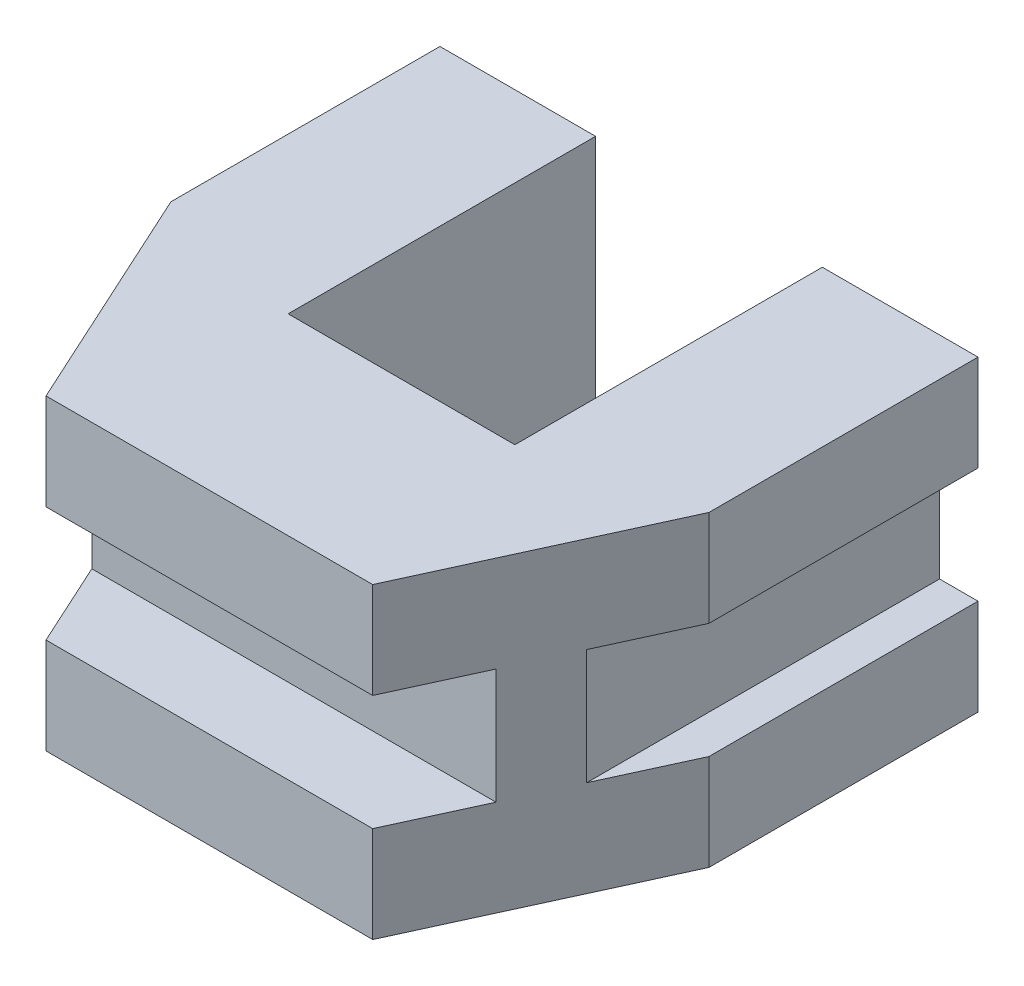
SolidWorks part; units mm, degrees
material "PUR"
ref_plane "Front" through (0, 0, 0) normal (0, 0, 1) x (1, 0, 0)
ref_plane "Top" through (0, 0, 0) normal (0, 1, 0) x (1, 0, 0)
ref_plane "Right" through (0, 0, 0) normal (1, 0, 0) x (0, 0, -1)
sketch "Sketch1" plane through (0, 0, 0) normal (0, 1, 0) x (1, 0, 0)
  line L0 (-7, 13) -> (-7, 6)
  line L1 (-7, 6) -> (-4.25, 0)
  line L3 (0, 0) -> (0, 7.9484) construction
  line L7 (4.25, 0) -> (-4.25, 0)
  line L8 (-7, 13) -> (-2.95, 13)
  line L9 (-2.95, 13) -> (-2.95, 5)
  line L10 (-2.95, 5) -> (2.95, 5)
  line L11 (2.95, 13) -> (2.95, 5)
  line L12 (7, 13) -> (2.95, 13)
  line L13 (7, 6) -> (4.25, 0)
  line L14 (7, 13) -> (7, 6)
  point P10 (0, 5)
  dimension "D1" = 14
  dimension "D2" = 13
  dimension "D3" = 8
  dimension "D4" = 5.9
  dimension "D5" = 7
  dimension "D6" = 8.5
extrude "Boss-Extrude1" add sketch "Sketch1" along normal mid plane 8
sketch "Sketch2" plane through (0, 0, 0) normal (1, 0, 0) x (0, 0, -1)
  line L0 (0, 4) -> (0, -4) construction
  line L1 (0, 1.5) -> (2.2, 1.5)
  line L2 (0, 1.5) -> (0, -1.5)
  line L3 (0, -1.5) -> (2.2, -1.5)
  line L4 (2.2, 1.5) -> (2.2, -1.5)
  dimension "D1" = 2.2
  dimension "D2" = 3
extrude "Cut-Extrude1" cut sketch "Sketch2" against normal through all both and the other way through all
sketch "Sketch3" plane through (0, 0, 0) normal (0, 0, 1) x (1, 0, 0)
  line L0 (-7, 4) -> (-7, -4) construction
  line L1 (-7, 1.5) -> (-6, 1.5)
  line L2 (-7, 1.5) -> (-7, -1.5)
  line L3 (-7, -1.5) -> (-6, -1.5)
  line L4 (-6, 1.5) -> (-6, -1.5)
  line L5 (0, 4) -> (0, 0) construction
  line L6 (-4.25, 4) -> (4.25, 4) construction
  line L7 (6, 1.5) -> (6, -1.5)
  line L8 (7, -1.5) -> (6, -1.5)
  line L9 (7, 1.5) -> (7, -1.5)
  line L10 (7, 1.5) -> (6, 1.5)
  point P6 (-6, 0)
  dimension "D1" = 12
  dimension "D2" = 3
extrude "Cut-Extrude2" cut sketch "Sketch3" against normal through all
